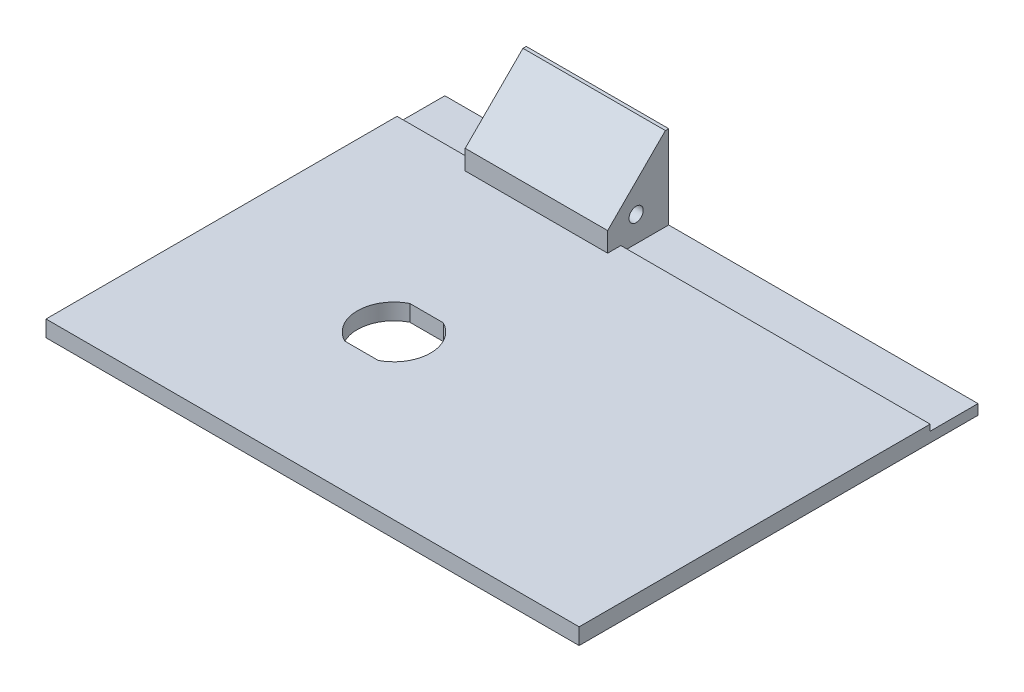
SolidWorks part; units mm, degrees
ref_plane "Ebene vorne" through (0, 0, 0) normal (0, 0, 1) x (1, 0, 0)
ref_plane "Ebene oben" through (0, 0, 0) normal (0, 1, 0) x (1, 0, 0)
ref_plane "Ebene rechts" through (0, 0, 0) normal (1, 0, 0) x (0, 0, -1)
sketch "Sketch1" plane through (0, 0, 0) normal (0, 1, 0) x (1, 0, 0)
  line L1 (65.5, -49) -> (-65.5, -49)
  line L2 (65.5, -49) -> (65.5, 49)
  line L3 (65.5, 49) -> (-65.5, 49)
  line L4 (-65.5, -49) -> (-65.5, 49)
  line L5 (65.5, -49) -> (-65.5, 49) construction
  line L6 (65.5, 49) -> (-65.5, -49) construction
  point P0 (0, 0)
  dimension "D1" = 131
  dimension "D2" = 98
extrude "Boss-Extrude1" add sketch "Sketch1" along normal blind 4
sketch "Lock" plane through (0, 4, 0) normal (0, 1, 0) x (1, 0, 0)
  line L0 (-24.1231, -1) -> (-15.8769, -1)
  line L1 (-24.1231, -17) -> (-15.8769, -17)
  line L2 (-20, -1) -> (-20, -12.568) construction
  line L3 (-65.5, -49) -> (65.5, -49) construction
  line L4 (-20, -45.8205) -> (-20, -27.3505) construction
  arc A0 (-24.1231, -1) -> (-24.1231, -17) centre (-20, -9) ccw
  arc A1 (-15.8769, -17) -> (-15.8769, -1) centre (-20, -9) ccw
  dimension "D1" = 9
  dimension "D3" = 40
  dimension "D2" = 16
  dimension "D4" = 45.5
extrude "Lock Hole" cut sketch "Lock" against normal through all
sketch "Sketch6" plane through (-65.5, 0, 0) normal (-1, 0, 0) x (0, 0, 1)
  line L1 (-49, 4) -> (-37.25, 4)
  line L2 (-49, 4) -> (-49, 2.5)
  line L3 (-49, 2.5) -> (-37.25, 2.5)
  line L4 (-37.25, 4) -> (-37.25, 2.5)
  dimension "D1" = 1.5
  dimension "D2" = 11.75
extrude "Cut-Extrude4" cut sketch "Sketch6" against normal up to surface (131 mm away) up to face at (65.5, 2, 0)
sketch "Sketch3" plane through (0, 4, 0) normal (0, 1, 0) x (1, 0, 0)
  line L0 (65.5, 49) -> (-65.5, 49) construction
  line L6 (65.5, 49) -> (-65.5, 49) construction
  line L7 (-45.5, 49) -> (-10.5, 49)
  line L8 (-45.5, 49) -> (-45.5, 34)
  line L9 (-45.5, 34) -> (-10.5, 34)
  line L10 (-10.5, 49) -> (-10.5, 34)
  dimension "D1" = 15
  dimension "D2" = 20
  dimension "D3" = 35
extrude "Boss-Extrude2" add sketch "Sketch3" along normal blind 19
sketch "Sketch4" plane through (-45.5, 0, 0) normal (-1, 0, 0) x (0, 0, 1)
  line L0 (-49, 0) -> (49, 0) construction
  line L1 (-49, 23) -> (-49, 4) construction
  circle A0 centre (-41, 8.75) radius 1.75
  dimension "D1" = 3.5
  dimension "D2" = 8.75
  dimension "D3" = 8
extrude "Cut-Extrude2" cut sketch "Sketch4" against normal up to surface (35 mm away) up to face at (-10.5, 11.6, -40.65)
sketch "Sketch5" plane through (-45.5, 0, 0) normal (-1, 0, 0) x (0, 0, 1)
  line L0 (-34, 8.8117) -> (-48.1883, 23)
  line L1 (-34, 23) -> (-34, 4) construction
  line L2 (-49, 23) -> (-34, 23) construction
  line L3 (-48.1883, 23) -> (-34, 23)
  line L4 (-34, 23) -> (-34, 8.8117)
  dimension "D2" = 45
extrude "Cut-Extrude3" cut sketch "Sketch5" against normal through all both and the other way through all
sketch "Sketch7" plane through (0, 0, -49) normal (0, 0, -1) x (-1, 0, 0)
  line L0 (-65.5, 2.5) -> (65.5, 2.5) construction
  line L1 (45.5, 4) -> (10.5, 4)
  line L2 (45.5, 4) -> (45.5, 2.5)
  line L3 (45.5, 2.5) -> (10.5, 2.5)
  line L4 (10.5, 4) -> (10.5, 2.5)
  line L5 (10.5, 23) -> (10.5, 4) construction
extrude "Boss-Extrude3" add sketch "Sketch7" against normal up to surface (11.75 mm away) up to face at (-9.3333, 3.5, -37.25)
